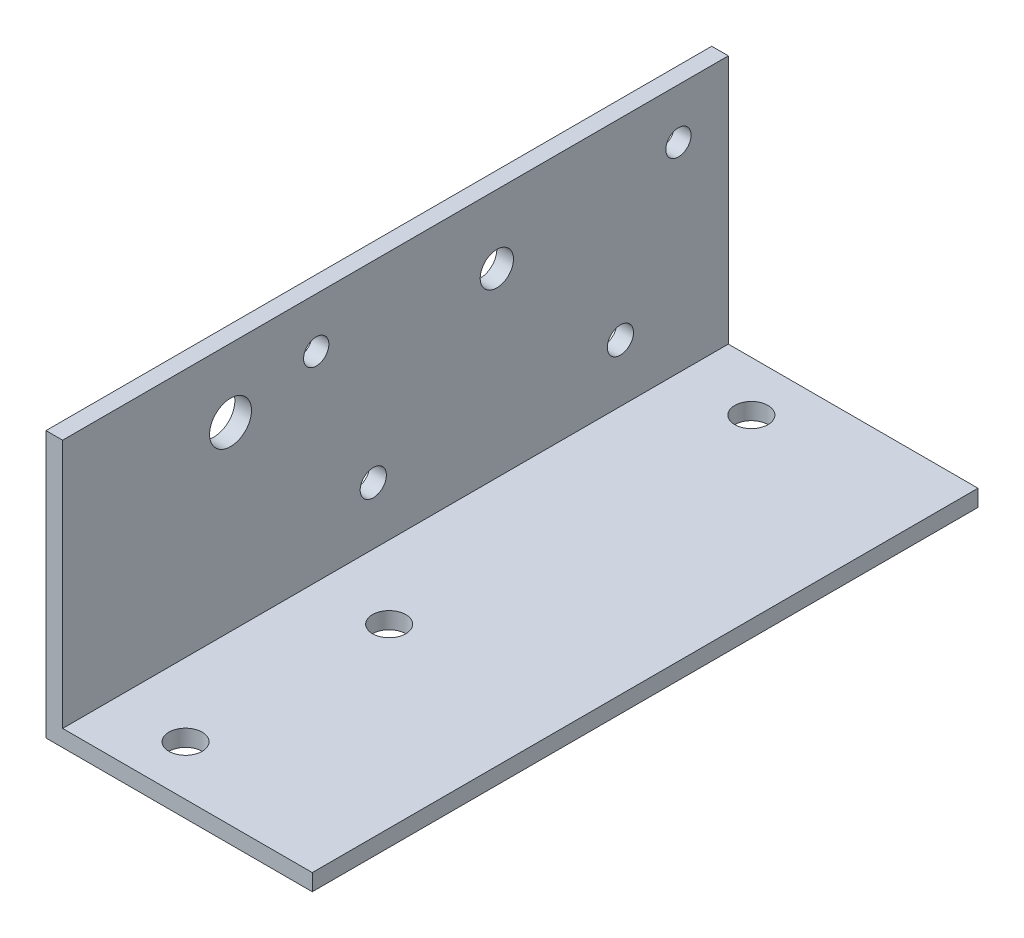
SolidWorks part; units mm, degrees
ref_plane "Front Plane" through (0, 0, 0) normal (0, 0, 1) x (1, 0, 0)
ref_plane "Top Plane" through (0, 0, 0) normal (0, 1, 0) x (1, 0, 0)
ref_plane "Right Plane" through (0, 0, 0) normal (1, 0, 0) x (0, 0, -1)
sketch "Sketch2" plane through (0, 0, 0) normal (0, 0, 1) x (1, 0, 0)
  line L0 (0, 0) -> (0, 50.8)
  line L1 (0, 50.8) -> (3.175, 50.8)
  line L2 (3.175, 50.8) -> (3.175, 3.175)
  line L3 (3.175, 3.175) -> (50.8, 3.175)
  line L4 (50.8, 3.175) -> (50.8, 0)
  line L5 (50.8, 0) -> (0, 0)
  dimension "D1" = 3.175
  dimension "D2" = 3.175
  dimension "D3" = 50.8
  dimension "D4" = 50.8
extrude "Boss-Extrude1" add sketch "Sketch2" along normal blind 127
sketch "Sketch3" plane through (0, 3.175, 0) normal (0, 1, 0) x (1, 0, 0)
  line L0 (17.0942, 0) -> (17.0942, -127) construction
  line L1 (50.8, 0) -> (3.175, 0) construction
  line L2 (50.8, -127) -> (3.175, -127) construction
  line L3 (3.175, -127) -> (3.175, 0) construction
  line L4 (0, -44.069) -> (50.8, -44.069) construction
  line L5 (0, -127) -> (0, 0) construction
  line L6 (50.8, -127) -> (50.8, 0) construction
  circle A0 centre (17.0942, -9.525) radius 3.175
  circle A1 centre (17.0942, -78.625) radius 3.175
  circle A2 centre (17.0942, -117.475) radius 3.175
  dimension "D2" = 6.35
  dimension "D1" = 13.9192
  dimension "D3" = 9.525
  dimension "D4" = 9.525
  dimension "D5" = 69.1
  dimension "D6" = 34.544
extrude "Cut-Extrude1" cut sketch "Sketch3" against normal through all
sketch "Sketch4" plane through (0, 0, 0) normal (-1, 0, 0) x (0, 0, 1)
  line L0 (0, 50.8) -> (0, 0) construction
  line L1 (127, 50.8) -> (0, 50.8) construction
  line L2 (127, 0) -> (0, 0) construction
  line L3 (44.1706, 0) -> (44.1706, 50.8) construction
  line L4 (44.1706, 37.725) -> (127, 37.725) construction
  line L5 (127, 50.8) -> (127, 0) construction
  circle A0 centre (20.5994, 14.155) radius 2.5
  circle A1 centre (9.525, 41.275) radius 2.413
  circle A2 centre (67.7394, 14.155) radius 2.5
  circle A3 centre (78.625, 41.275) radius 2.413
  circle A4 centre (44.1706, 37.725) radius 3.175
  circle A5 centre (94.9706, 37.725) radius 4
  dimension "D1" = 5
  dimension "D2" = 6.35
  dimension "D7" = 4.826
  dimension "D12" = 8
  dimension "D3" = 47.14
  dimension "D4" = 69.1
  dimension "D5" = 9.525
  dimension "D6" = 9.525
  dimension "D8" = 14.155
  dimension "D9" = 44.1706
  dimension "D10" = 47.1424
  dimension "D11" = 23.57
  dimension "D13" = 50.8
extrude "Cut-Extrude2" cut sketch "Sketch4" against normal through all
